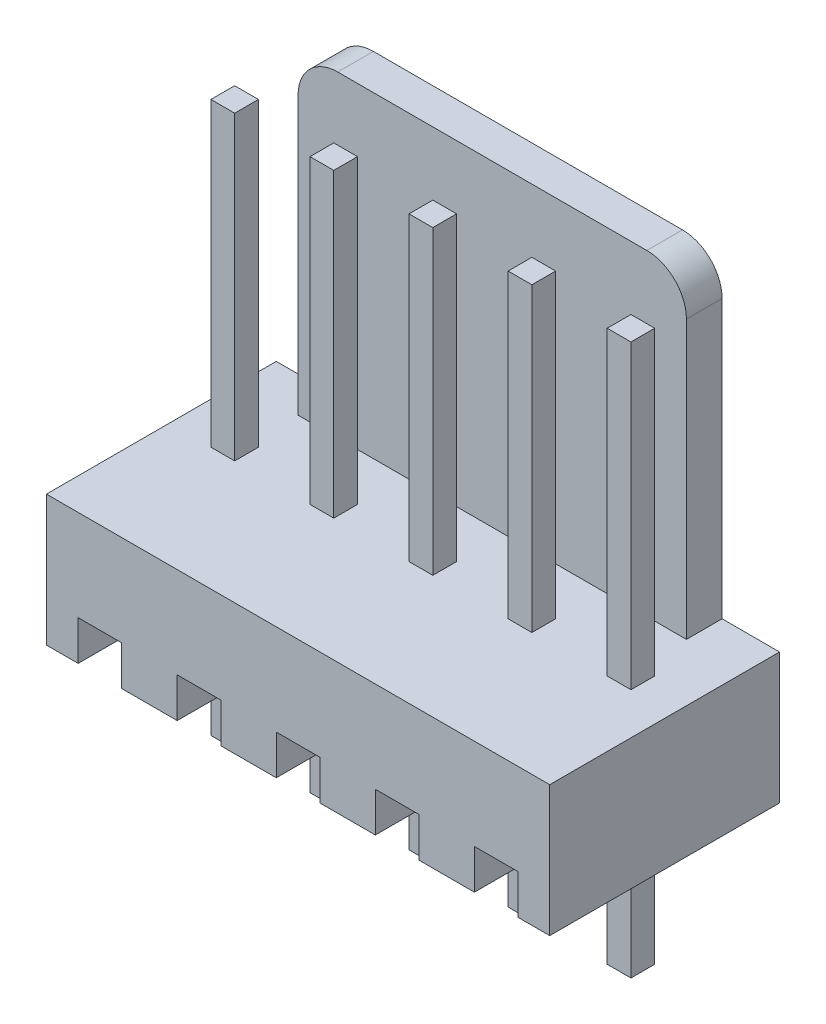
SolidWorks part; units mm, degrees
ref_plane "Alzado" through (0, 0, 0) normal (0, 0, 1) x (1, 0, 0)
ref_plane "Planta" through (0, 0, 0) normal (0, 1, 0) x (1, 0, 0)
ref_plane "Vista lateral" through (0, 0, 0) normal (1, 0, 0) x (0, 0, -1)
sketch "Croquis1" plane through (0, 0, 0) normal (0, 1, 0) x (1, 0, 0)
  line L1 (-6.35, 2.9) -> (6.35, 2.9)
  line L2 (-6.35, 2.9) -> (-6.35, -2.9)
  line L3 (-6.35, -2.9) -> (6.35, -2.9)
  line L4 (6.35, 2.9) -> (6.35, -2.9)
  line L5 (-6.35, 2.9) -> (6.35, -2.9) construction
  line L6 (-6.35, -2.9) -> (6.35, 2.9) construction
  point P0 (0, 0)
  dimension "D1" = 12.7
  dimension "D2" = 5.8
extrude "Saliente-Extruir1" add sketch "Croquis1" along normal blind 3.3
sketch "Croquis2" plane through (0, 3.3, 0) normal (0, 1, 0) x (1, 0, 0)
  line L0 (-6.35, 2.9) -> (-4.9, 2.9) construction
  line L1 (6.35, 2.9) -> (-6.35, 2.9) construction
  line L2 (-4.9, 2.9) -> (4.9, 2.9) construction
  line L3 (4.9, 2.9) -> (6.35, 2.9) construction
  line L4 (-4.9, 2.9) -> (4.9, 2.9)
  line L5 (-4.9, 2.9) -> (-4.9, 2)
  line L6 (4.9, 2.9) -> (4.9, 2)
  line L7 (-4.9, 2) -> (4.9, 2)
  dimension "D1" = 1.45
  dimension "D2" = 9.8
  dimension "D3" = 1.45
  dimension "D4" = 0.9
extrude "Saliente-Extruir2" add sketch "Croquis2" along normal blind 8
fillet "Redondeo1" radius 1 2 edges at (4.9, 11.3, -2.45)
fillet "Redondeo2" radius 1 2 edges at (-4.9, 11.3, -2.45)
sketch "Croquis3" plane through (0, 0, 0) normal (0, -1, 0) x (1, 0, 0)
  line L0 (-6.35, 2.9) -> (-5.55, 2.9) construction
  line L1 (-6.35, 2.9) -> (6.35, 2.9) construction
  line L2 (-5.55, 2.9) -> (-4.45, 2.9) construction
  line L3 (-4.45, 2.9) -> (-3.05, 2.9) construction
  line L4 (-3.05, 2.9) -> (-1.95, 2.9) construction
  line L5 (-1.95, 2.9) -> (-0.55, 2.9) construction
  line L6 (-0.55, 2.9) -> (0.55, 2.9) construction
  line L7 (1.95, 2.9) -> (3.05, 2.9) construction
  line L8 (3.05, 2.9) -> (4.45, 2.9) construction
  line L9 (4.45, 2.9) -> (5.55, 2.9) construction
  line L10 (5.55, 2.9) -> (6.35, 2.9) construction
  line L12 (-6.35, -2.9) -> (6.35, -2.9) construction
  line L13 (-5.55, 2.9) -> (-4.45, 2.9)
  line L14 (-4.45, 2.9) -> (-4.45, -2.9)
  line L15 (-4.45, -2.9) -> (-5.55, -2.9)
  line L16 (-5.55, -2.9) -> (-5.55, 2.9)
  line L17 (-3.05, 2.9) -> (-3.05, -2.9)
  line L18 (-3.05, -2.9) -> (-1.95, -2.9)
  line L19 (-1.95, -2.9) -> (-1.95, 2.9)
  line L20 (-1.95, 2.9) -> (-3.05, 2.9)
  line L21 (-0.55, 2.9) -> (0.55, 2.9)
  line L22 (0.55, 2.9) -> (0.55, -2.9)
  line L23 (0.55, -2.9) -> (-0.55, -2.9)
  line L24 (-0.55, -2.9) -> (-0.55, 2.9)
  line L25 (1.95, 2.9) -> (3.05, 2.9)
  line L26 (3.05, 2.9) -> (3.05, -2.9)
  line L27 (3.05, -2.9) -> (1.95, -2.9)
  line L28 (1.95, -2.9) -> (1.95, 2.9)
  line L29 (4.45, 2.9) -> (5.55, 2.9)
  line L30 (5.55, 2.9) -> (5.55, -2.9)
  line L31 (5.55, -2.9) -> (4.45, -2.9)
  line L32 (4.45, -2.9) -> (4.45, 2.9)
  dimension "D1" = 0.8
  dimension "D2" = 1.1
  dimension "D3" = 1.1
  dimension "D4" = 1.1
  dimension "D5" = 1.1
  dimension "D6" = 1.1
  dimension "D7" = 1.4
  dimension "D8" = 1.4
  dimension "D9" = 1.4
  dimension "D10" = 1.4
  dimension "D11" = 0.8
  dimension "D12" = 12.7
extrude "Cortar-Extruir1" cut sketch "Croquis3" against normal blind 1
sketch "Croquis4" plane through (0, 1, 0) normal (0, -1, 0) x (-1, 0, 0)
  line L0 (5.55, -2.9) -> (5.55, 0.8) construction
  line L1 (5.55, -2.9) -> (5.55, 2.9) construction
  line L2 (5.55, 0.8) -> (5.3, 0.8) construction
  line L3 (5.3, 0.8) -> (4.7, 0.8) construction
  line L4 (4.7, 0.8) -> (4.45, 0.8) construction
  line L5 (4.45, 2.9) -> (4.45, -2.9) construction
  line L6 (4.7, 0.8) -> (5.3, 0.8)
  line L7 (4.7, 0.8) -> (4.7, 0.2)
  line L8 (5.3, 0.8) -> (5.3, 0.2)
  line L9 (4.7, 0.2) -> (5.3, 0.2)
  line L10 (3.05, -2.9) -> (3.05, 0.8) construction
  line L11 (3.05, -2.9) -> (3.05, 2.9) construction
  line L12 (3.05, 0.8) -> (2.8, 0.8) construction
  line L13 (2.8, 0.8) -> (2.2, 0.8) construction
  line L14 (2.2, 0.8) -> (1.95, 0.8) construction
  line L15 (1.95, 2.9) -> (1.95, -2.9) construction
  line L16 (2.8, 0.8) -> (2.2, 0.8)
  line L17 (2.8, 0.8) -> (2.8, 0.2)
  line L18 (2.2, 0.8) -> (2.2, 0.2)
  line L19 (2.8, 0.2) -> (2.2, 0.2)
  line L20 (0.55, -2.9) -> (0.55, 0.8) construction
  line L21 (0.55, -2.9) -> (0.55, 2.9) construction
  line L22 (0.55, 0.8) -> (0.3, 0.8) construction
  line L23 (0.3, 0.8) -> (-0.3, 0.8) construction
  line L24 (-0.3, 0.8) -> (-0.55, 0.8) construction
  line L25 (-0.55, 2.9) -> (-0.55, -2.9) construction
  line L26 (-0.3, 0.8) -> (0.3, 0.8)
  line L27 (-0.3, 0.8) -> (-0.3, 0.2)
  line L28 (0.3, 0.8) -> (0.3, 0.2)
  line L29 (-0.3, 0.2) -> (0.3, 0.2)
  line L30 (-1.95, -2.9) -> (-1.95, 0.8) construction
  line L31 (-1.95, -2.9) -> (-1.95, 2.9) construction
  line L32 (-1.95, 0.8) -> (-2.2, 0.8) construction
  line L33 (-2.2, 0.8) -> (-2.8, 0.8) construction
  line L34 (-2.8, 0.8) -> (-3.05, 0.8) construction
  line L35 (-3.05, 2.9) -> (-3.05, -2.9) construction
  line L36 (-2.8, 0.8) -> (-2.2, 0.8)
  line L37 (-2.8, 0.8) -> (-2.8, 0.2)
  line L38 (-2.2, 0.8) -> (-2.2, 0.2)
  line L39 (-2.8, 0.2) -> (-2.2, 0.2)
  line L40 (-4.45, -2.9) -> (-4.45, 0.8) construction
  line L41 (-4.45, -2.9) -> (-4.45, 2.9) construction
  line L42 (-4.45, 0.8) -> (-4.7, 0.8) construction
  line L43 (-4.7, 0.8) -> (-5.3, 0.8) construction
  line L44 (-5.3, 0.8) -> (-5.55, 0.8) construction
  line L45 (-5.55, 2.9) -> (-5.55, -2.9) construction
  line L46 (-5.3, 0.8) -> (-4.7, 0.8)
  line L47 (-5.3, 0.8) -> (-5.3, 0.2)
  line L48 (-4.7, 0.8) -> (-4.7, 0.2)
  line L49 (-5.3, 0.2) -> (-4.7, 0.2)
  dimension "D1" = 3.7
  dimension "D2" = 0.6
  dimension "D3" = 0.25
  dimension "D4" = 0.25
  dimension "D5" = 0.6
  dimension "D6" = 3.7
  dimension "D7" = 0.6
  dimension "D8" = 0.25
  dimension "D9" = 0.25
  dimension "D10" = 0.6
  dimension "D11" = 3.7
  dimension "D12" = 0.6
  dimension "D13" = 0.25
  dimension "D14" = 0.25
  dimension "D15" = 0.6
  dimension "D16" = 3.7
  dimension "D17" = 0.25
  dimension "D18" = 0.6
  dimension "D19" = 0.25
  dimension "D20" = 0.6
  dimension "D21" = 3.7
  dimension "D22" = 0.25
  dimension "D23" = 0.6
  dimension "D24" = 0.25
  dimension "D25" = 0.6
extrude "Saliente-Extruir3" add sketch "Croquis4" along normal blind 4 and the other way blind 9.9
